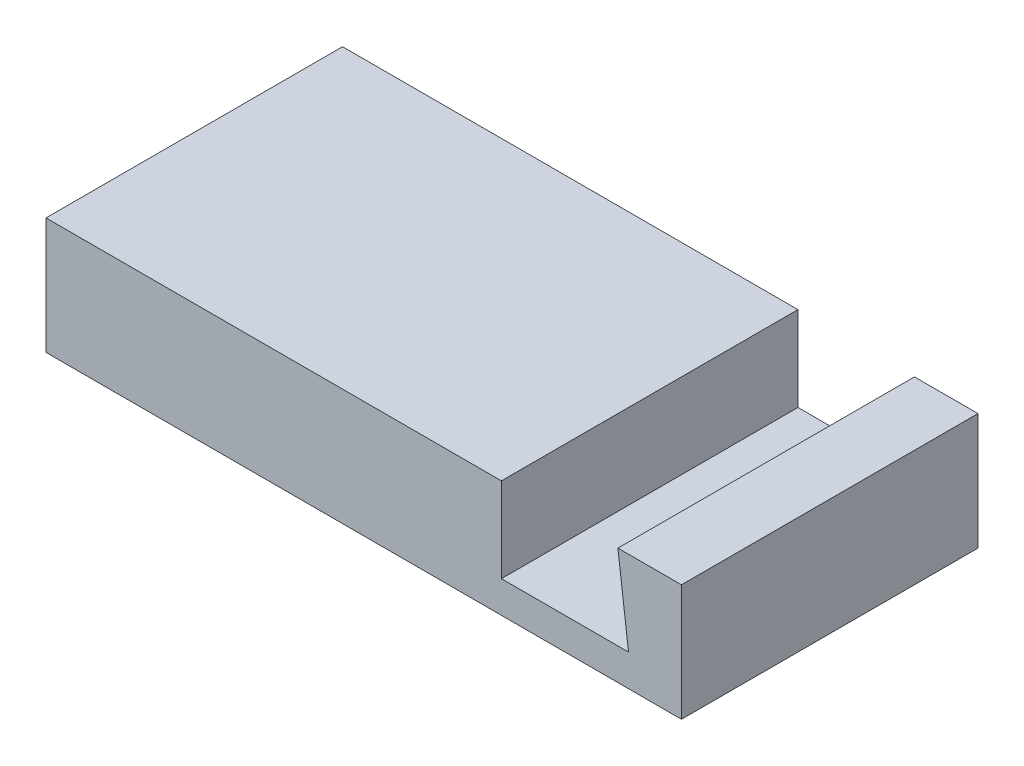
SolidWorks part; units mm, degrees
ref_plane "Alzado" through (0, 0, 0) normal (0, 0, 1) x (1, 0, 0)
ref_plane "Planta" through (0, 0, 0) normal (0, 1, 0) x (1, 0, 0)
ref_plane "Vista lateral" through (0, 0, 0) normal (1, 0, 0) x (0, 0, -1)
sketch "Croquis1" plane through (0, 0, 0) normal (0, 0, 1) x (1, 0, 0)
  line L0 (0, 0) -> (60, 0)
  line L1 (60, 0) -> (60, 11)
  line L2 (60, 11) -> (54, 11)
  line L3 (54, 11) -> (55, 3)
  line L4 (55, 3) -> (43, 3)
  line L5 (43, 3) -> (43, 11)
  line L6 (43, 11) -> (0, 11)
  line L7 (0, 11) -> (0, 0)
  dimension "D1" = 60
  dimension "D2" = 11
  dimension "D3" = 11
  dimension "D4" = 6
  dimension "D5" = 12
  dimension "D6" = 3
extrude "Saliente-Extruir1" add sketch "Croquis1" along normal blind 28
